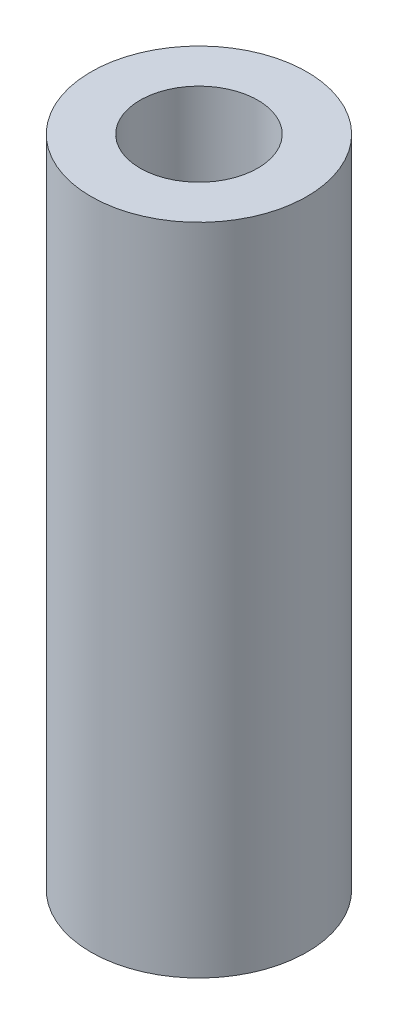
SolidWorks part; units mm, degrees
ref_plane "Front Plane" through (0, 0, 0) normal (0, 0, 1) x (1, 0, 0)
ref_plane "Top Plane" through (0, 0, 0) normal (0, 1, 0) x (1, 0, 0)
ref_plane "Right Plane" through (0, 0, 0) normal (1, 0, 0) x (0, 0, -1)
sketch "Sketch1" plane through (0, 0, 0) normal (0, 1, 0) x (1, 0, 0)
  circle A0 centre (0, 0) radius 1.8
  circle A1 centre (0, 0) radius 3.3
  dimension "D1" = 3.6
  dimension "D2" = 1.5
extrude "Boss-Extrude1" add sketch "Sketch1" along normal blind 20
